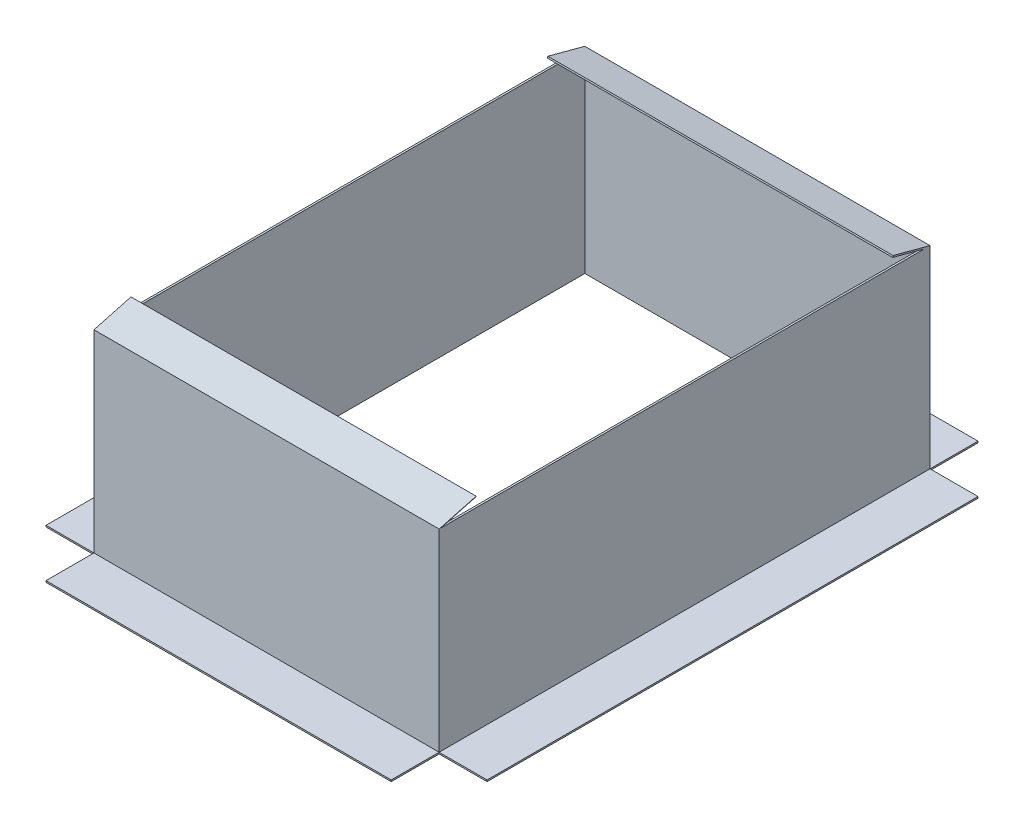
SolidWorks part; units mm, degrees
ref_plane "Front Plane" through (0, 0, 0) normal (0, 0, 1) x (1, 0, 0)
ref_plane "Top Plane" through (0, 0, 0) normal (0, 1, 0) x (1, 0, 0)
ref_plane "Right Plane" through (0, 0, 0) normal (1, 0, 0) x (0, 0, -1)
ref_plane "Plane1"
sketch "Sketch1" plane through (0, 0, 0) normal (0, 1, 0) x (-1, 0, 0)
  line L0 (90, 128) -> (-90, 128)
  line L1 (-90, 128) -> (-90, -128)
  line L2 (-90, -128) -> (90, -128)
  line L3 (90, -128) -> (90, 128)
  line L4 (-89, 127) -> (89, 127)
  line L5 (89, 127) -> (89, -127)
  line L6 (89, -127) -> (-89, -127)
  line L7 (-89, -127) -> (-89, 127)
  dimension "D1" = 178
  dimension "D2" = 254
extrude "Extrusion1" add sketch "Sketch1" along normal blind 101.6 contours L2 L3 L0 L1 L6 L7 L4 L5
ref_plane "Plane2" through (0, 0, 0) normal (0, -1, 0) x (1, 0, 0)
sketch "Sketch2" plane through (0, 0, 0) normal (0, -1, 0) x (1, 0, 0)
  line L0 (90, 128) -> (90, 153)
  line L1 (90, 153) -> (-90, 153)
  line L2 (-90, 153) -> (-90, 128)
  line L3 (-90, 128) -> (90, 128)
  line L4 (90, -128) -> (-90, -128)
  line L5 (-90, -128) -> (-90, -153)
  line L6 (-90, -153) -> (90, -153)
  line L7 (90, -153) -> (90, -128)
  line L8 (90, 128) -> (90, -128)
  line L9 (90, -128) -> (115, -128)
  line L10 (115, -128) -> (115, 128)
  line L11 (115, 128) -> (90, 128)
  line L12 (-90, -128) -> (-90, 128)
  line L13 (-90, 128) -> (-115, 128)
  line L14 (-115, 128) -> (-115, -128)
  line L15 (-115, -128) -> (-90, -128)
  dimension "D1" = 25
  dimension "D2" = 25
  dimension "D3" = 25
  dimension "D4" = 25
extrude "Extrusion3" add sketch "Sketch2" against normal blind 0.8 contours L2 L3 L0 L1 | L6 L7 L4 L5 | L10 L11 L8 L9 | L14 L15 L12 L13
ref_plane "Plane3" through (101.5, 0.8, -139.5) normal (0, 1, 0) x (0, 0, -1)
hole_wizard "Hole1" positions "Sketch4" profile "Sketch3"
sketch "Sketch4" plane through (101.5, 0.8, -139.5) normal (0, 1, 0) x (0, 0, -1)
  point P1 (0, 0)
  point P2 (-34.875, 0)
  point P3 (-104.625, 0)
  point P4 (-174.375, 0)
  point P5 (-244.125, 0)
  point P6 (-279, 0)
  point P7 (0, 33.8333)
  point P8 (0, 101.5)
  point P9 (0, 169.1667)
  point P10 (0, 203)
  point P11 (-279, 33.8333)
  point P12 (-279, 101.5)
  point P13 (-279, 169.1667)
  point P14 (-279, 203)
  point P15 (-34.875, 203)
  point P16 (-104.625, 203)
  point P17 (-174.375, 203)
  point P18 (-244.125, 203)
sketch "Sketch3" plane through (101.5, 0.8, -139.5) normal (1, 0, 0) x (0, 0, 1)
  line L0 (0, 0) -> (0, 0.8)
  line L1 (0, 0.8) -> (3, 0.8)
  line L2 (3, 0.8) -> (3, 0)
  line L3 (3, 0) -> (0, 0)
  line L4 (0, 110) -> (0, -10) construction
  dimension "Diameter" = 6
  dimension "Depth" = 0.8
sketch "Sketch5" plane through (90, 0, 0) normal (1, 0, 0) x (0, 0, -1)
  line L0 (-128, 101.6) -> (-127.2, 101.6)
  line L1 (-127.2, 101.6) -> (-108.6279, 106.5764)
  line L2 (-108.6279, 106.5764) -> (-108.6815, 106.7764)
  line L3 (-108.6815, 106.7764) -> (-128, 101.6)
  line L4 (124.909, 101.6) -> (128, 101.6)
  line L5 (128, 101.6) -> (108.6815, 106.7764)
  line L6 (108.6815, 106.7764) -> (108.4744, 106.0036)
  line L7 (108.4744, 106.0036) -> (124.909, 101.6)
  line L8 (-128, 101.6) -> (128, 101.6) construction
  dimension "D1" = 20
  dimension "D2" = 20
  dimension "D3" = 15
extrude "Extrusion10" add sketch "Sketch5" against normal up to surface up to face at (-90, 0.4, 140.5)
